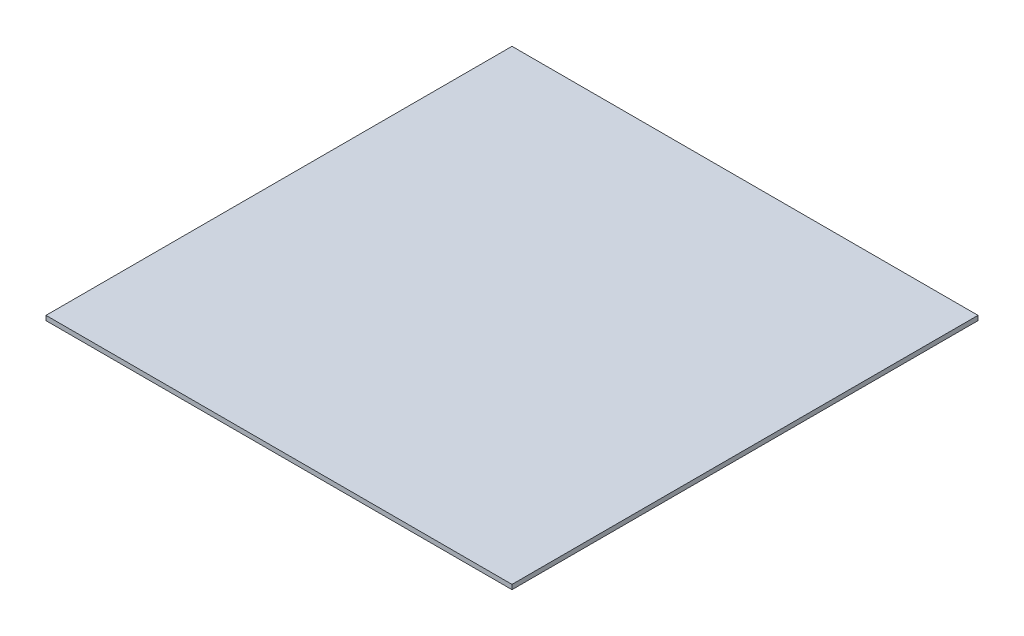
SolidWorks part; units mm, degrees
material "6061-T6 (SS)"
ref_plane "Alzado" through (0, 0, 0) normal (0, 0, 1) x (1, 0, 0)
ref_plane "Planta" through (0, 0, 0) normal (0, 1, 0) x (1, 0, 0)
ref_plane "Vista lateral" through (0, 0, 0) normal (1, 0, 0) x (0, 0, -1)
sketch "Sketch1" plane through (0, 0, 0) normal (0, 1, 0) x (1, 0, 0)
  line L1 (-101, 101) -> (101, 101)
  line L2 (-101, 101) -> (-101, -101)
  line L3 (-101, -101) -> (101, -101)
  line L4 (101, 101) -> (101, -101)
  line L5 (-101, 101) -> (101, -101) construction
  line L6 (-101, -101) -> (101, 101) construction
  point P0 (0, 0)
  dimension "D1" = 202
  dimension "D2" = 202
extrude "Boss-Extrude1" add sketch "Sketch1" along normal blind 2
